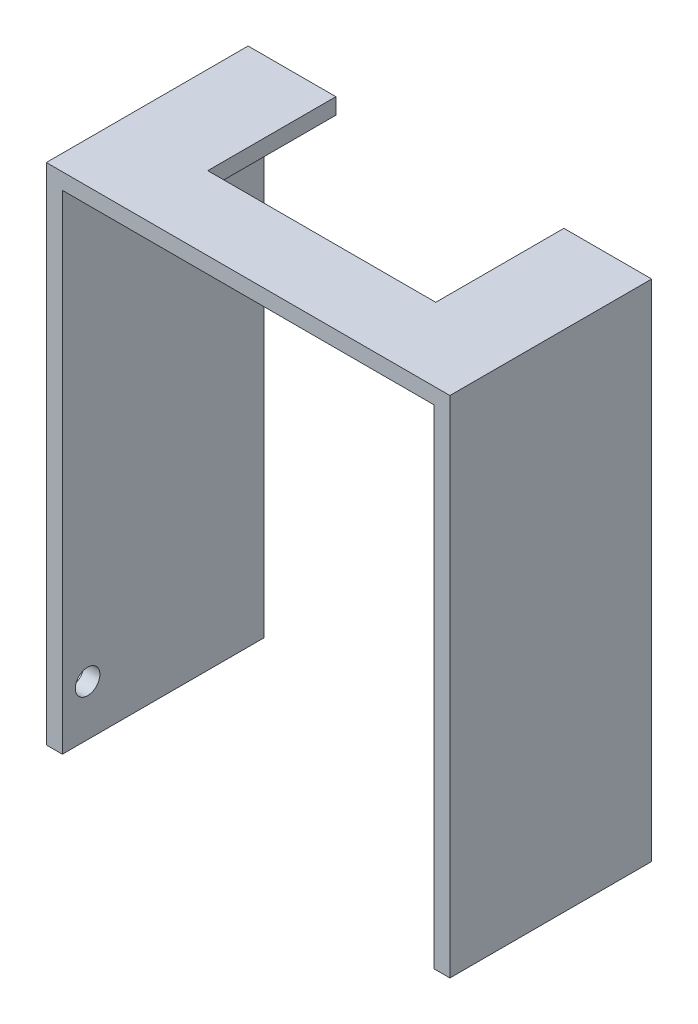
SolidWorks part; units mm, degrees
ref_plane "Front Plane" through (0, 0, 0) normal (0, 0, 1) x (1, 0, 0)
ref_plane "Top Plane" through (0, 0, 0) normal (0, 1, 0) x (1, 0, 0)
ref_plane "Right Plane" through (0, 0, 0) normal (1, 0, 0) x (0, 0, -1)
sketch "Sketch1" plane through (0, 0, 0) normal (0, 0, 1) x (1, 0, 0)
  line L0 (1.59, -50) -> (1.59, -1.59)
  line L1 (0, -50) -> (0, 0)
  line L2 (0, 0) -> (40, 0)
  line L3 (40, 0) -> (40, -50)
  line L4 (1.59, -1.59) -> (38.41, -1.59)
  line L5 (38.41, -1.59) -> (38.41, -50)
  line L6 (0, -50) -> (1.59, -50)
  line L7 (38.41, -50) -> (40, -50)
  dimension "D1" = 40
  dimension "D2" = 1.59
  dimension "D3" = 50
extrude "Boss-Extrude1" add sketch "Sketch1" along normal blind 20
sketch "Sketch2" plane through (0, 0, 0) normal (0, 1, 0) x (1, 0, 0)
  line L0 (8.7, 0) -> (8.7, -12.7)
  line L1 (40, 0) -> (0, 0) construction
  line L2 (8.7, -12.7) -> (31.3, -12.7)
  line L3 (31.3, -12.7) -> (31.3, 0)
  line L5 (20, 0) -> (20, -12.7) construction
  line L6 (8.7, 0) -> (31.3, 0)
  dimension "D1" = 22.6
  dimension "D2" = 12.7
extrude "Cut-Extrude1" cut sketch "Sketch2" against normal blind 10
hole_wizard "#2 Clearance Hole1" positions "Sketch4" profile "Sketch5" hole size "#2" standard "ANSI Inch"
sketch "Sketch4" plane through (0, 0, 0) normal (-1, 0, 0) x (0, 0, 1)
  line L0 (20, 0) -> (0, 0) construction
  point P0 (2.5, -5)
  point P2 (17.5, -45)
  dimension "D1" = 5
  dimension "D2" = 40
  dimension "D3" = 15
  dimension "D4" = 2.5
sketch "Sketch5" plane through (0, -5, 2.5) normal (0, 1, 0) x (0, 0, 1)
  line L0 (0, 0) -> (0, 2.3216)
  line L1 (0, 2.3216) -> (1.2192, 1.589)
  line L2 (1.2192, 1.589) -> (1.2192, 0)
  line L5 (1.2192, 0) -> (0, 0)
  line L10 (0, 2.3216) -> (-1.2192, 1.589) construction
  line L11 (0, -6.35) -> (0, 107.95) construction
  dimension "Hole Dia." = 2.4384
  dimension "Hole Depth" = 1.589
  dimension "Drill Angle" = 118
